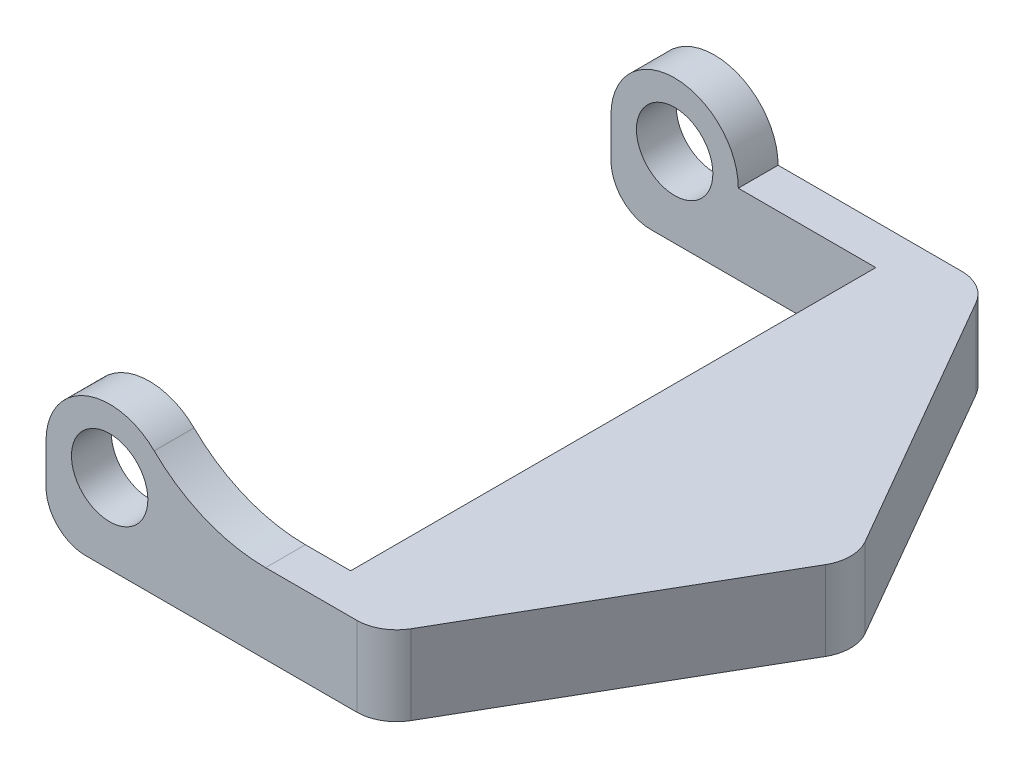
SolidWorks part; units mm, degrees
ref_plane "Front Plane" through (0, 0, 0) normal (0, 0, 1) x (1, 0, 0)
ref_plane "Top Plane" through (0, 0, 0) normal (0, 1, 0) x (1, 0, 0)
ref_plane "Right Plane" through (0, 0, 0) normal (1, 0, 0) x (0, 0, -1)
sketch "Sketch1" plane through (0, 0, 0) normal (0, 1, 0) x (1, 0, 0)
  line L0 (10.9697, 19) -> (21.9393, 0)
  line L5 (-10.9697, -19) -> (10.9697, -19) construction
  line L6 (-10.9697, -19) -> (-10.9697, 19) construction
  line L7 (-10.9697, 19) -> (10.9697, 19) construction
  line L8 (10.9697, -19) -> (10.9697, 19) construction
  line L9 (-10.9697, -19) -> (10.9697, 19) construction
  line L10 (-10.9697, 19) -> (10.9697, -19) construction
  line L11 (21.9393, 0) -> (10.9697, -19)
  line L12 (0, -19) -> (0, 19) construction
  line L13 (0, 19) -> (10.9697, 19)
  line L14 (0, -19) -> (10.9697, -19)
  line L15 (6.6395, 16.5) -> (16.1658, 0) construction
  line L16 (16.1658, 0) -> (6.6395, -16.5) construction
  line L17 (6.6395, 16.5) -> (-10, 16.5)
  line L18 (-10, 16.5) -> (-10, 19)
  line L19 (-10, 19) -> (0, 19)
  line L20 (6.6395, -16.5) -> (-10, -16.5)
  line L21 (-10, -16.5) -> (-10, -19)
  line L22 (-10, -19) -> (0, -19)
  line L23 (6.6395, 16.5) -> (6.6395, -16.5)
  point P0 (0, 0)
  point P1 (0, 0)
  dimension "D1" = 120
  dimension "D2" = 35.5
  dimension "D4" = 10
  dimension "D3" = 2.5
extrude "Boss-Extrude1" add sketch "Sketch1" along normal blind 5
sketch "Sketch2" plane through (0, 0, 19) normal (0, 0, 1) x (1, 0, 0)
  line L0 (-10, 5) -> (10.9697, 5) construction
  line L1 (-10, 5) -> (-2, 5)
  arc A0 (-2, 5) -> (-10, 5) centre (-6, 5) ccw
  point P1 (0, 0)
  point P4 (-4.3103, 5)
  dimension "D1" = 4
extrude "Boss-Extrude2" add sketch "Sketch2" against normal blind 2.5
mirror "Mirror1" about plane through (0, 0, 0) normal (0, 0, 1) of "Boss-Extrude2"
sketch "Sketch3" plane through (0, 0, 19) normal (0, 0, 1) x (1, 0, 0)
  line L0 (-10, 5) -> (-2, 5) construction
  arc A0 (-2, 5) -> (-10, 5) centre (-6, 5) ccw construction
  arc A1 (-2, 5) -> (-10, 5) centre (-6, 5) ccw construction
  circle A2 centre (-6, 5) radius 7.3826
  point P0 (-6, 5)
hole_wizard "M4 Clearance Hole2" positions "3DSketch1" profile "Sketch7" hole size "M4" standard "ANSI Metric" end condition through all
sketch3d "3DSketch1"
  point P0 (-6, 5, 19)
sketch "Sketch7" plane through (-6, 5, 19) normal (1, 0, 0) x (0, -1, 0)
  line L0 (0, 0) -> (0, 38)
  line L1 (0, 38) -> (2.4, 38)
  line L2 (2.4, 38) -> (2.4, 0)
  line L5 (2.4, 0) -> (0, 0)
  line L11 (0, -6.35) -> (0, 107.95) construction
  dimension "Thru Hole Dia." = 4.8
  dimension "Thru Hole Depth" = 38
fillet "Fillet1" radius 10 1 edges at (-2, 5, 17.75)
fillet "Fillet2" radius 2.5 5 edges at (-10, 0, -17.75) (-10, 0, 17.75) (10.9697, 2.5, -19) (10.9697, 2.5, 19) (21.9393, 2.5, 0)
